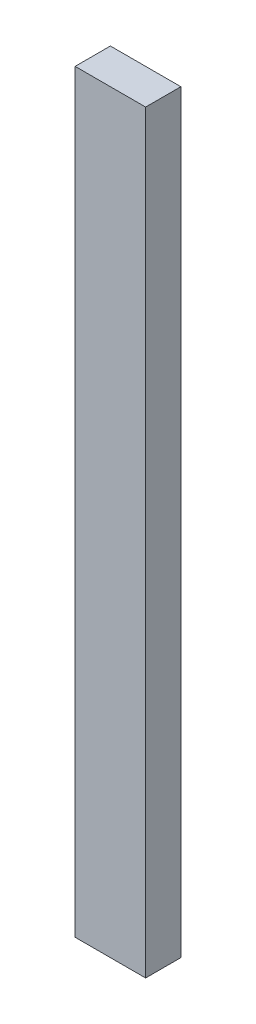
SolidWorks part; units mm, degrees
ref_plane "Front Plane" through (0, 0, 0) normal (0, 0, 1) x (1, 0, 0)
ref_plane "Top Plane" through (0, 0, 0) normal (0, 1, 0) x (1, 0, 0)
ref_plane "Right Plane" through (0, 0, 0) normal (1, 0, 0) x (0, 0, -1)
sketch "Sketch1" plane through (0, 0, 0) normal (0, 1, 0) x (1, 0, 0)
  line L1 (-237.3333, 75) -> (-197.3333, 75)
  line L2 (-237.3333, 75) -> (-237.3333, 55)
  line L3 (-237.3333, 55) -> (-197.3333, 55)
  line L4 (-197.3333, 75) -> (-197.3333, 55)
  dimension "D1" = 40
  dimension "D2" = 20
extrude "Boss-Extrude1" add sketch "Sketch1" along normal blind 428
